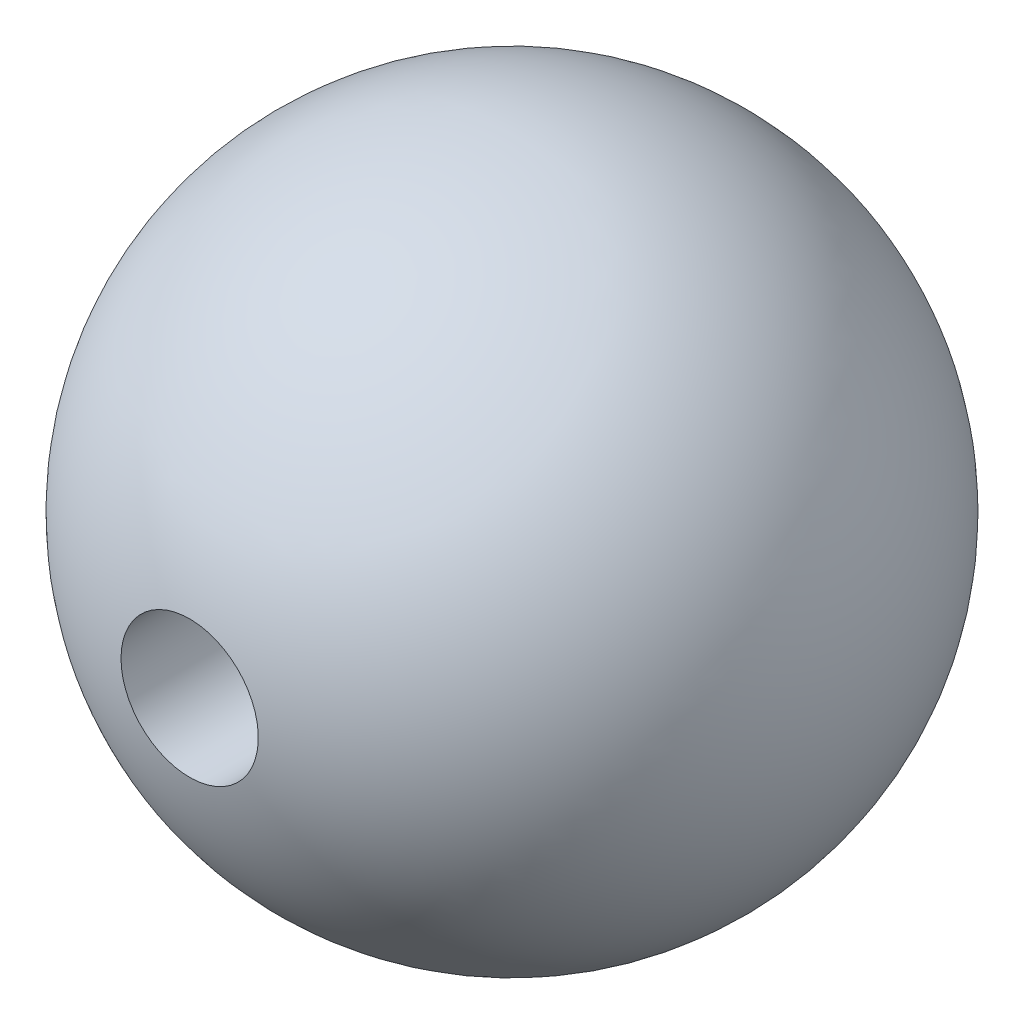
SolidWorks part; units mm, degrees
ref_plane "Plan1" through (0, 0, 0) normal (0, 0, 1) x (1, 0, 0)
ref_plane "Plan2" through (0, 0, 0) normal (0, 1, 0) x (1, 0, 0)
ref_plane "Plan3" through (0, 0, 0) normal (1, 0, 0) x (0, 0, -1)
sketch "Esquisse2" plane through (0, 0, 0) normal (0, 0, 1) x (1, 0, 0)
  line L0 (-11.2, 0) -> (78.8, 0) construction
  line L1 (1.2, 0) -> (-1.2, 0)
  arc A0 (1.2, 0) -> (-1.2, 0) centre (0, 0) ccw
  dimension "D1" = 1.2
revolve "Base-Révolution" add sketch "Esquisse2" angle 360 about L0
sketch "Esquisse3" plane through (0, 0, 0) normal (0, 0, 1) x (1, 0, 0)
  circle A0 centre (0, 0) radius 0.25
  dimension "D1" = 0.5
extrude "Enlèv. mat.-Extru.1" cut sketch "Esquisse3" against normal mid plane 10
